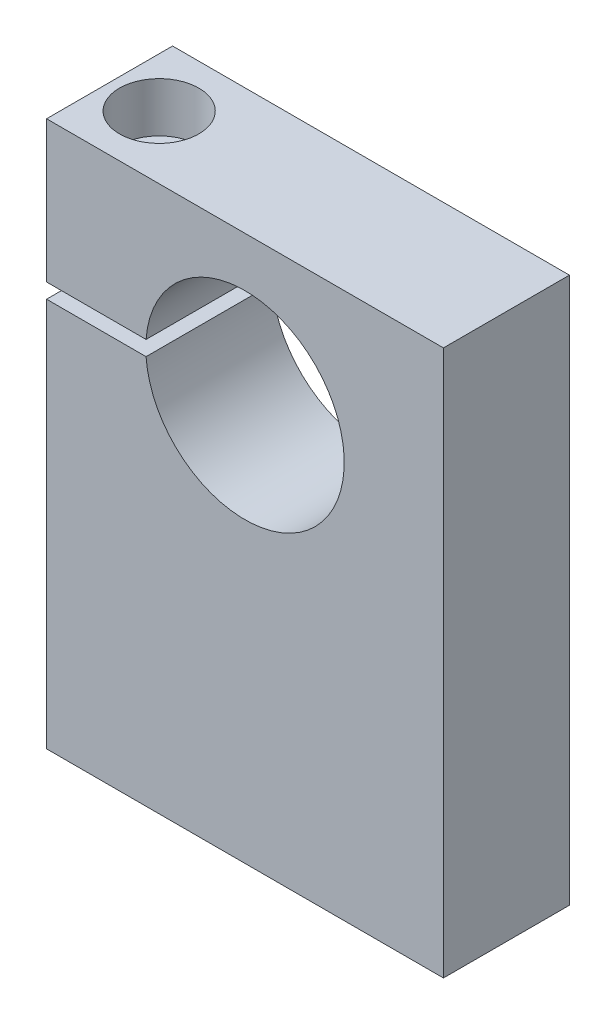
SolidWorks part; units mm, degrees
material "Aleación 1060"
ref_plane "Alzado" through (0, 0, 0) normal (0, 0, 1) x (1, 0, 0)
ref_plane "Planta" through (0, 0, 0) normal (0, 1, 0) x (1, 0, 0)
ref_plane "Vista lateral" through (0, 0, 0) normal (1, 0, 0) x (0, 0, -1)
sketch "Croquis1" plane through (0, 0, 0) normal (0, 0, 1) x (1, 0, 0)
  line L0 (20, 15) -> (-20, 15) construction
  line L1 (20, 40) -> (-20, 40) construction
  line L2 (20, 40) -> (20, -40) construction
  line L3 (20, -40) -> (-20, -40) construction
  line L4 (-20, 40) -> (-20, -40) construction
  line L5 (20, 40) -> (-20, -40) construction
  line L6 (20, -40) -> (-20, 40) construction
  line L7 (-20, 0.75) -> (-20, 15)
  line L8 (26.4676, -0.75) -> (-26.4676, -0.75) construction
  line L9 (26.4676, -0.75) -> (26.4676, 0.75) construction
  line L10 (26.4676, 0.75) -> (-26.4676, 0.75) construction
  line L11 (-26.4676, -0.75) -> (-26.4676, 0.75) construction
  line L12 (26.4676, -0.75) -> (-26.4676, 0.75) construction
  line L13 (26.4676, 0.75) -> (-26.4676, -0.75) construction
  line L14 (-20, 15) -> (20, 15)
  line L15 (20, 15) -> (20, -40)
  line L16 (20, -40) -> (-20, -40)
  line L17 (-20, -40) -> (-20, -0.75)
  line L18 (-20, -0.75) -> (-9.9718, -0.75)
  line L19 (-20, 0.75) -> (-9.9718, 0.75)
  circle A0 centre (0, 0) radius 10 construction
  arc A1 (-9.9718, -0.75) -> (-9.9718, 0.75) centre (0, 0) ccw
  point P9 (0, 15)
  point P14 (-20, 0.75)
  dimension "D1" = 80
  dimension "D2" = 40
  dimension "D3" = 55
  dimension "D4" = 1.5
  dimension "D5" = 52.9353
extrude "Saliente-Extruir1" add sketch "Croquis1" along normal blind 12.7 contours A1 L18 L17 L16 L15 L14 L7 L19
sketch "Croquis2" plane through (0, 15, 0) normal (0, 1, 0) x (1, 0, 0)
  circle A0 centre (-15.001, -6.35) radius 2
extrude "Cortar-Extruir1" cut sketch "Croquis2" against normal blind 23
sketch "Croquis3" plane through (0, 15, 0) normal (0, 1, 0) x (1, 0, 0)
  circle A0 centre (-15.001, -6.35) radius 4
extrude "Cortar-Extruir2" cut sketch "Croquis3" against normal blind 5
sketch "Croquis4" plane through (0, -40, 0) normal (0, -1, 0) x (1, 0, 0)
  line L0 (-20, 12.7) -> (-20, 0) construction
  circle A0 centre (-12.5, 6.35) radius 3.9688
  circle A1 centre (12.5, 6.35) radius 3.9688
  dimension "D1" = 25
  dimension "D2" = 7.5
extrude "Cortar-Extruir3" cut sketch "Croquis4" against normal blind 15
